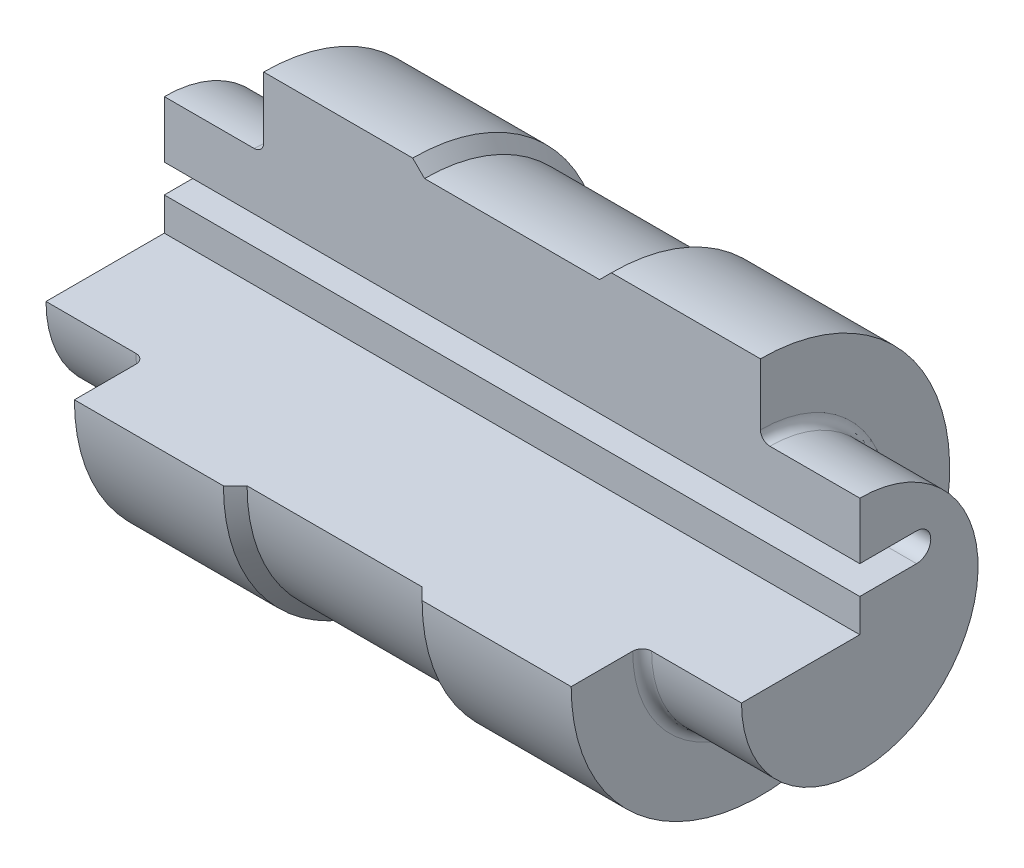
SolidWorks part; units mm, degrees
material "AISI 1020"
ref_plane "Plan de face" through (0, 0, 0) normal (0, 0, 1) x (1, 0, 0)
ref_plane "Plan de dessus" through (0, 0, 0) normal (0, 1, 0) x (1, 0, 0)
ref_plane "Plan de droite" through (0, 0, 0) normal (1, 0, 0) x (0, 0, -1)
sketch "Esquisse1" plane through (0, 0, 0) normal (0, 0, 1) x (1, 0, 0)
  line L0 (0, 0) -> (-117.7281, 0)
  line L1 (-117.7281, 0) -> (-117.7281, 25)
  line L2 (-117.7281, 25) -> (-96.7281, 25)
  line L3 (-96.7281, 25) -> (-96.7281, 40)
  line L4 (-96.7281, 40) -> (-65.2281, 40)
  line L5 (-65.2281, 40) -> (-62.7281, 37.5)
  line L6 (-62.7281, 37.5) -> (-25.7281, 37.5)
  line L7 (-25.7281, 37.5) -> (-23.2281, 40)
  line L8 (-23.2281, 40) -> (8.2719, 40)
  line L9 (8.2719, 40) -> (8.2719, 25)
  line L10 (8.2719, 25) -> (29.2719, 25)
  line L11 (29.2719, 25) -> (29.2719, 0)
  line L12 (29.2719, 0) -> (0, 0)
  line L13 (-65.2281, 40) -> (-65.2281, 30.1665) construction
  line L14 (-23.2281, 40) -> (-23.2281, 23.5403) construction
  dimension "D1" = 40
  dimension "D2" = 25
  dimension "D3" = 25
  dimension "D4" = 40
  dimension "D5" = 147
  dimension "D6" = 45
  dimension "D7" = 45
  dimension "D8" = 2.5
  dimension "D9" = 31.5
  dimension "D10" = 21
revolve "Révolution1" add sketch "Esquisse1" angle 270 about L0
sketch "Esquisse3" plane through (-117.7281, 0, 0) normal (-1, 0, 0) x (0, 0, 1)
  line L0 (-12, 10) -> (0, 10) construction
  line L1 (0, 25) -> (0, 0) construction
  line L2 (-12, 13) -> (0, 13)
  line L3 (-12, 7) -> (0, 7)
  arc A0 (-12, 13) -> (-12, 7) centre (-12, 10) ccw
  arc A1 (0, 7) -> (0, 13) centre (0, 10) ccw
  point P4 (-6, 10)
  dimension "D2" = 3
  dimension "D1" = 7
  dimension "D3" = 12
extrude "Enlèv. mat.-Extru.1" cut sketch "Esquisse3" against normal through all both and the other way through all
fillet "Congé1" radius 2 2 edges at (8.2719, -17.6777, -17.6777) (-96.7281, -17.6777, -17.6777)
sketch "Esquisse4" plane through (-117.7281, 0, 0) normal (-1, 0, 0) x (0, 0, 1)
  arc A0 (0, 25) -> (25, 0) centre (0, 0) ccw construction
  arc A1 (0, 40) -> (40, 0) centre (0, 0) ccw construction
  arc A2 (0, 25) -> (25, 0) centre (0, 0) ccw
  arc A3 (0, 40) -> (40, 0) centre (0, 0) ccw
sketch "Esquisse5" plane through (0, 0, 0) normal (0, 1, 0) x (1, 0, 0)
  line L12 (29.2719, 0) -> (-117.7281, 0)
  line L13 (-117.7281, 0) -> (-117.7281, -25)
  line L14 (-117.7281, -25) -> (-98.7281, -25)
  line L15 (-96.7281, -27) -> (-96.7281, -40)
  line L16 (-96.7281, -40) -> (-65.2281, -40)
  line L17 (-65.2281, -40) -> (-62.7281, -37.5)
  line L18 (-62.7281, -37.5) -> (-25.7281, -37.5)
  line L19 (-25.7281, -37.5) -> (-23.2281, -40)
  line L20 (-23.2281, -40) -> (8.2719, -40)
  line L21 (8.2719, -40) -> (8.2719, -27)
  line L22 (10.2719, -25) -> (29.2719, -25)
  line L23 (29.2719, -25) -> (29.2719, 0)
  line L24 (29.2719, 0) -> (-117.7281, 0)
  line L25 (-117.7281, 0) -> (-117.7281, -25)
  line L26 (-117.7281, -25) -> (-98.7281, -25)
  line L27 (-96.7281, -27) -> (-96.7281, -40)
  line L28 (-96.7281, -40) -> (-65.2281, -40)
  line L29 (-65.2281, -40) -> (-62.7281, -37.5)
  line L30 (-62.7281, -37.5) -> (-25.7281, -37.5)
  line L31 (-25.7281, -37.5) -> (-23.2281, -40)
  line L32 (-23.2281, -40) -> (8.2719, -40)
  line L33 (8.2719, -40) -> (8.2719, -27)
  line L34 (10.2719, -25) -> (29.2719, -25)
  line L35 (29.2719, -25) -> (29.2719, 0)
  arc A2 (-96.7281, -27) -> (-98.7281, -25) centre (-98.7281, -27) ccw
  arc A3 (10.2719, -25) -> (8.2719, -27) centre (10.2719, -27) ccw
  arc A4 (-96.7281, -27) -> (-98.7281, -25) centre (-98.7281, -27) ccw
  arc A5 (10.2719, -25) -> (8.2719, -27) centre (10.2719, -27) ccw
  dimension "D1" = 0
equation "\"A\"= 147"
equation "\"B\"=21"
equation "\"C\"=31.5"
equation "\"D5@Esquisse1\"=\"A\""
equation "\"D9@Esquisse1\"=\"C\""
equation "\"D10@Esquisse1\"=\"B\""
